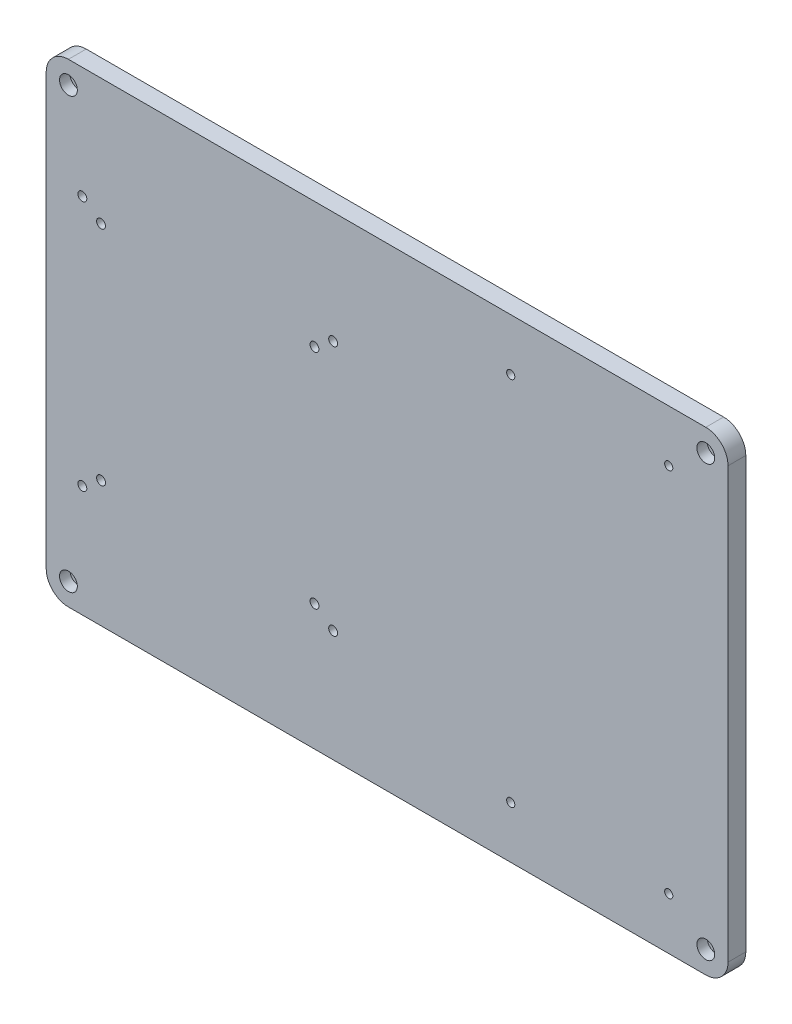
SolidWorks part; units mm, degrees
ref_plane "Front Plane" through (0, 0, 0) normal (0, 0, 1) x (1, 0, 0)
ref_plane "Top Plane" through (0, 0, 0) normal (0, 1, 0) x (1, 0, 0)
ref_plane "Right Plane" through (0, 0, 0) normal (1, 0, 0) x (0, 0, -1)
sketch "Sketch1" plane through (0, 0, 0) normal (0, 0, 1) x (1, 0, 0)
  line L1 (-107.5, 80) -> (107.5, 80)
  line L2 (-115, 72.5) -> (-115, -72.5)
  line L3 (-107.5, -80) -> (107.5, -80)
  line L4 (115, 72.5) -> (115, -72.5)
  line L5 (-115, 80) -> (115, -80) construction
  line L6 (-115, -80) -> (115, 80) construction
  arc A0 (-115, -72.5) -> (-107.5, -80) centre (-107.5, -72.5) ccw
  arc A1 (107.5, -80) -> (115, -72.5) centre (107.5, -72.5) ccw
  arc A2 (107.5, 80) -> (115, 72.5) centre (107.5, 72.5) cw
  arc A3 (-107.5, 80) -> (-115, 72.5) centre (-107.5, 72.5) ccw
  point P0 (0, 0)
  dimension "D3" = 7.5
  dimension "D1" = 230
  dimension "D2" = 160
extrude "Boss-Extrude1" add sketch "Sketch1" along normal blind 6
sketch "Sketch2" plane through (0, 0, 6) normal (0, 0, 1) x (1, 0, 0)
  line L0 (-115, 72.5) -> (-115, -72.5) construction
  line L1 (-107.5, -80) -> (107.5, -80) construction
  line L2 (107.5, 80) -> (-107.5, 80) construction
  line L3 (115, -72.5) -> (115, 72.5) construction
  circle A0 centre (-107.5, -72.5) radius 1.75
  circle A1 centre (-107.5, 72.5) radius 1.75
  circle A2 centre (107.5, -72.5) radius 1.75
  circle A3 centre (107.5, 72.5) radius 1.75
  dimension "D1" = 7.5
  dimension "D3" = 3.5
  dimension "D4" = 3.5
  dimension "D7" = 3.5
  dimension "D10" = 3.5
  dimension "D2" = 7.5
  dimension "D5" = 7.5
  dimension "D6" = 7.5
  dimension "D8" = 7.5
  dimension "D9" = 7.5
  dimension "D11" = 7.5
  dimension "D12" = 7.5
extrude "Cut-Extrude1" cut sketch "Sketch2" against normal blind 10
sketch "Sketch3" plane through (0, 0, 6) normal (0, 0, 1) x (1, 0, 0)
  circle A0 centre (-107.5, -72.5) radius 3
  circle A1 centre (-107.5, 72.5) radius 3
  circle A2 centre (107.5, 72.5) radius 3
  circle A3 centre (107.5, -72.5) radius 3
  dimension "D1" = 6
  dimension "D2" = 6
  dimension "D3" = 6
  dimension "D4" = 6
extrude "Cut-Extrude2" cut sketch "Sketch3" against normal blind 3.5
sketch "Sketch4" plane through (0, 0, 6) normal (0, 0, 1) x (1, 0, 0)
  line L0 (107.5, 80) -> (-107.5, 80) construction
  line L3 (-115, 72.5) -> (-115, -72.5) construction
  line L4 (-107.5, -80) -> (107.5, -80) construction
  circle A0 centre (-96.5, 37.5) radius 1.5
  circle A1 centre (-96.5, -37.5) radius 1.5
  circle A2 centre (-24.5, 37.5) radius 1.5
  circle A3 centre (-24.5, -37.5) radius 1.5
  dimension "D2" = 3
  dimension "D3" = 3
  dimension "D6" = 3
  dimension "D7" = 3
  dimension "D1" = 75
  dimension "D4" = 42.5
  dimension "D5" = 18.5
  dimension "D8" = 72
  dimension "D9" = 72
  dimension "D10" = 42.5
  dimension "D11" = 42.5
extrude "Cut-Extrude3" cut sketch "Sketch4" against normal through all
sketch "Sketch5" plane through (0, 0, 6) normal (0, 0, 1) x (1, 0, 0)
  line L0 (-107.5, -80) -> (107.5, -80) construction
  line L2 (115, -72.5) -> (115, 72.5) construction
  circle A0 centre (95, -62.5) radius 1.375
  circle A1 centre (95, 62.5) radius 1.375
  circle A2 centre (41.7, -62.5) radius 1.375
  circle A3 centre (41.7, 62.5) radius 1.375
  dimension "D1" = 125
  dimension "D4" = 2.75
  dimension "D6" = 53.3
  dimension "D2" = 17.5
  dimension "D3" = 20
  dimension "D5" = 53.3
extrude "Cut-Extrude4" cut sketch "Sketch5" against normal through all and the other way through all
sketch "Sketch7" plane through (0, 0, 6) normal (0, 0, 1) x (1, 0, 0)
  circle A0 centre (-102.8, 42.3) radius 1.5
  circle A1 centre (-96.5, 37.5) radius 1.5 construction
  circle A2 centre (-102.8, -42.3) radius 1.5
  circle A3 centre (-18.2, -42.3) radius 1.5
  circle A4 centre (-18.2, 42.3) radius 1.5
  circle A5 centre (-96.5, -37.5) radius 1.5 construction
  circle A6 centre (-24.5, -37.5) radius 1.5 construction
  circle A7 centre (-24.5, 37.5) radius 1.5 construction
  dimension "D1" = 6.3
  dimension "D3" = 3
  dimension "D4" = 3
  dimension "D5" = 3
  dimension "D6" = 3
  dimension "D7" = 4.8
  dimension "D8" = 6.3
  dimension "D10" = 4.8
  dimension "D11" = 4.8
  dimension "D12" = 6.3
  dimension "D2" = 4.8
extrude "Cut-Extrude6" cut sketch "Sketch7" against normal through all
sketch "Sketch8" plane through (0, 0, 0) normal (0, 0, -1) x (-1, 0, 0)
  circle A0 centre (18.2, 42.3) radius 3
  circle A1 centre (18.2, -42.3) radius 3
  circle A2 centre (102.8, -42.3) radius 3
  circle A3 centre (102.8, 42.3) radius 3
  dimension "D1" = 6
  dimension "D2" = 6
  dimension "D3" = 6
  dimension "D4" = 6
extrude "Cut-Extrude7" cut sketch "Sketch8" against normal blind 3.5
